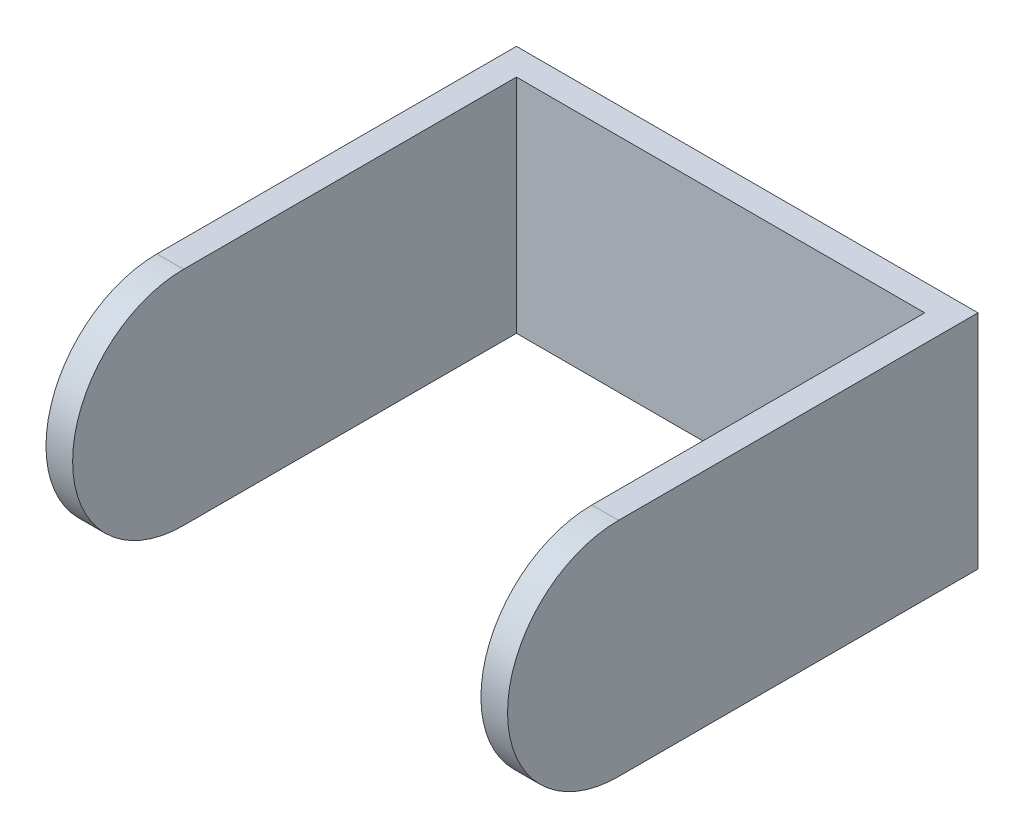
SolidWorks part; units mm, degrees
material "아크릴(내충격성)"
ref_plane "정면" through (0, 0, 0) normal (0, 0, 1) x (1, 0, 0)
ref_plane "윗면" through (0, 0, 0) normal (0, 1, 0) x (1, 0, 0)
ref_plane "우측면" through (0, 0, 0) normal (1, 0, 0) x (0, 0, -1)
sketch "스케치1" plane through (0, 0, 0) normal (0, 0, 1) x (1, 0, 0)
  line L3 (-26, 12.5) -> (26, 12.5)
  line L5 (-26, -12.5) -> (26, -12.5)
  line L6 (-26, 12.5) -> (-26, -12.5)
  line L7 (26, 12.5) -> (26, -12.5)
extrude "보스-돌출1" add sketch "스케치1" along normal blind 3
sketch "스케치2" plane through (0, 0, 3) normal (0, 0, 1) x (1, 0, 0)
  line L0 (-26, -12.5) -> (-26, 12.5)
  line L1 (-26, 12.5) -> (-23, 12.5)
  line L3 (26, 12.5) -> (-26, 12.5) construction
  line L4 (-23, 12.5) -> (-23, -12.5)
  line L5 (-26, -12.5) -> (26, -12.5) construction
  line L6 (-23, -12.5) -> (-26, -12.5)
  line L8 (23, -12.5) -> (26, -12.5)
  line L9 (23, 12.5) -> (23, -12.5)
  line L10 (26, 12.5) -> (23, 12.5)
  line L11 (26, -12.5) -> (26, 12.5)
extrude "보스-돌출2" add sketch "스케치2" along normal blind 50
sketch "스케치3" plane through (26, 0, 0) normal (1, 0, 0) x (0, 0, -1)
  line L5 (0, -12.5) -> (0, 12.5)
  line L6 (0, 12.5) -> (-53, 12.5)
  line L7 (-53, 12.5) -> (-53, -12.5)
  line L8 (-53, -12.5) -> (0, -12.5)
  line L10 (-40.5, 12.5) -> (-53, 12.5)
  line L11 (-53, 12.5) -> (-53, -12.5)
  line L12 (-53, -12.5) -> (-40.5, -12.5)
  arc A0 (-40.5, 12.5) -> (-40.5, -12.5) centre (-40.5, 0) ccw
  line M8 (0, 12.5) -> (-53, 12.5)
  line M9 (-53, 12.5) -> (-53, -12.5)
  line M10 (-53, -12.5) -> (0, -12.5)
  dimension "D1" = 0
extrude "컷-돌출1" cut sketch "스케치3" against normal through all contours A0 M8 M9 | A0 L11 M10
sketch "스케치5" plane through (0, 0, 0) normal (0, 0, -1) x (-1, 0, 0)
  circle A0 centre (0, 0) radius 10
  dimension "D1" = 20
sketch "스케치6" plane through (23, 0, 0) normal (-1, 0, 0) x (0, 0, 1)
  circle A0 centre (40.5, 0) radius 10
